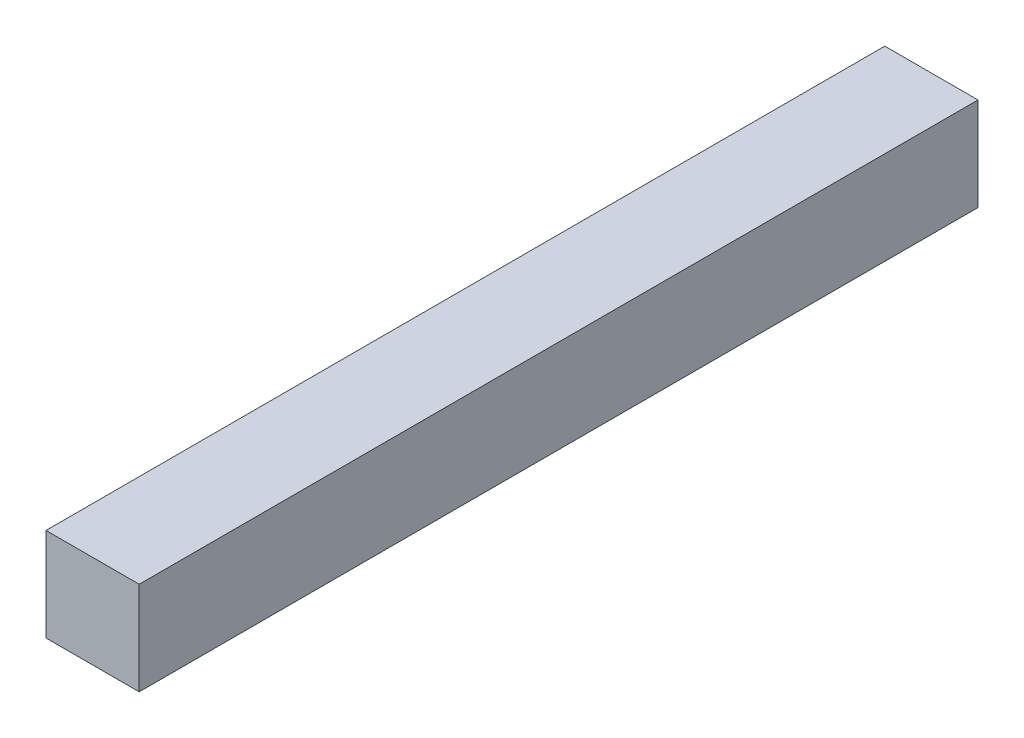
SolidWorks part; units mm, degrees
ref_plane "前基準面" through (0, 0, 0) normal (0, 0, 1) x (1, 0, 0)
ref_plane "上基準面" through (0, 0, 0) normal (0, 1, 0) x (1, 0, 0)
ref_plane "右基準面" through (0, 0, 0) normal (1, 0, 0) x (0, 0, -1)
sketch "草圖1" plane through (0, 0, 0) normal (0, 0, 1) x (1, 0, 0)
  line L1 (-10, 10) -> (10, 10)
  line L2 (-10, 10) -> (-10, -10)
  line L3 (-10, -10) -> (10, -10)
  line L4 (10, 10) -> (10, -10)
  point P4 (0, 10)
  point P6 (-10, 0)
  dimension "D1" = 20
  dimension "D2" = 20
extrude "填料-伸長1" add sketch "草圖1" along normal blind 180
